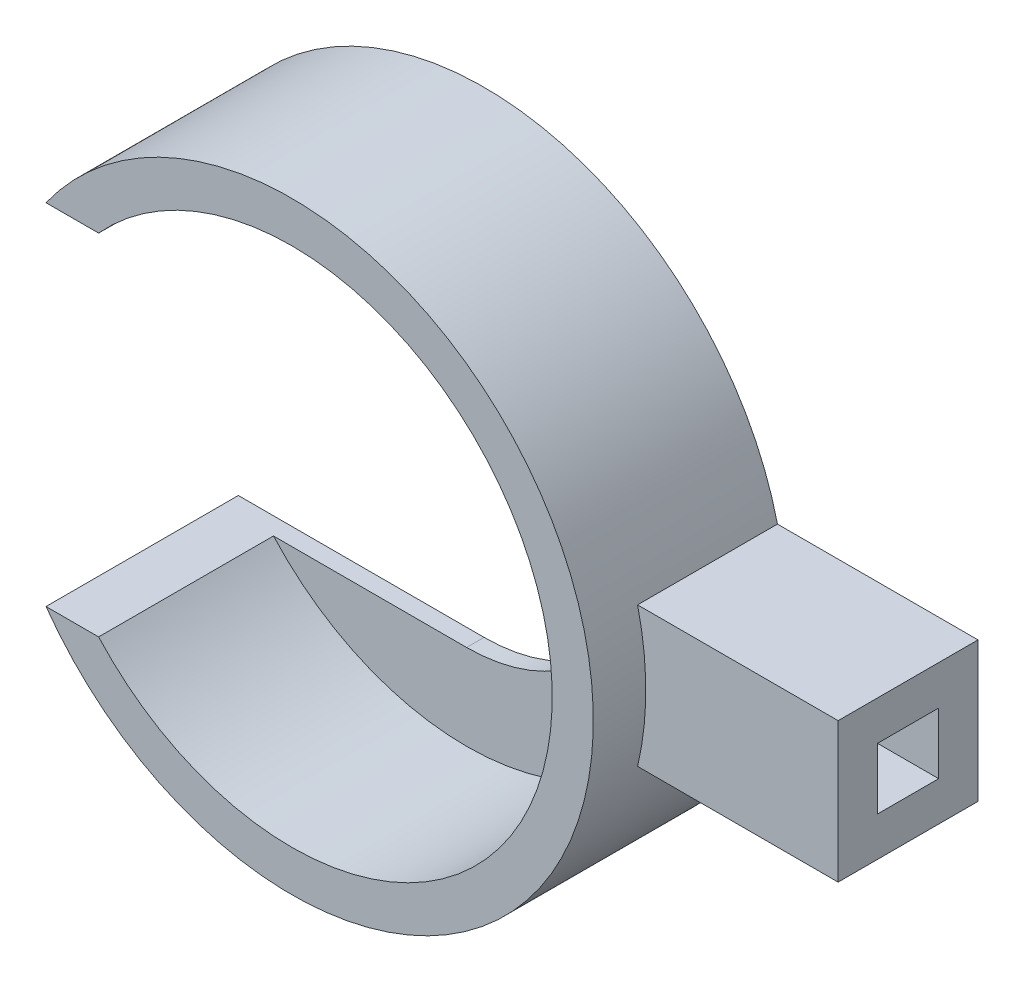
SolidWorks part; units mm, degrees
ref_plane "Front Plane" through (0, 0, 0) normal (0, 0, 1) x (1, 0, 0)
ref_plane "Top Plane" through (0, 0, 0) normal (0, 1, 0) x (1, 0, 0)
ref_plane "Right Plane" through (0, 0, 0) normal (1, 0, 0) x (0, 0, -1)
sketch "Sketch1" plane through (0, 0, 0) normal (0, 0, 1) x (1, 0, 0)
  circle A0 centre (0, 0) radius 14.9
  circle A1 centre (0, 0) radius 17.25
extrude "Boss-Extrude1" add sketch "Sketch1" along normal blind 10
sketch "Sketch2" plane through (0, 0, 0) normal (0, 0, -1) x (-1, 0, 0)
  circle A0 centre (0, 0) radius 17.25
  circle A1 centre (0, 0) radius 10
extrude "Boss-Extrude3" add sketch "Sketch2" along normal blind 1
sketch "Sketch3" plane through (0, 0, -1) normal (0, 0, -1) x (-1, 0, 0)
  line L0 (0, 10) -> (14.0557, 10)
  line L1 (0, -10) -> (14.0557, -10)
  circle A0 centre (0, 0) radius 10
  circle A1 centre (0, 0) radius 17.25 construction
  circle A2 centre (0, 0) radius 17.25
  circle M1 centre (0, 0) radius 17.25
  circle M2 centre (0, 0) radius 10
extrude "Cut-Extrude1" cut sketch "Sketch3" against normal through all contours M2 | L1 L0 M2 M1
sketch3d "3DSketch1"
  line L0 (17.25, 0, -1) -> (17.25, -4, -1)
  line L1 (17.25, 0, -1) -> (17.25, 4, -1)
  line L7 (17.25, 0, -1) -> (17.25, 0, 10) construction
  line L8 (17.25, 4, -1) -> (17.25, 4, 7)
  line L10 (17.25, 4, 7) -> (17.25, -4, 7)
  line L11 (17.25, -4, -1) -> (17.25, -4, 7)
  arc A0 (-14.0557, 10, -1) -> (-14.0557, -10, -1) centre (0, 0, -1) ccw construction
  arc A1 (-14.0557, -10, 10) -> (-14.0557, 10, 10) centre (0, 0, 10) ccw construction
  point P5 (0, 0, -18.25)
  point P9 (0, 0, 27.25)
extrude "Boss-Extrude4" add sketch "3DSketch1" along direction (-1, 0, 0) on the side of the normal blind 11 and the other way blind 1.5 contours L11 L10 L8 L1 L0
sketch "Sketch4" plane through (28.25, 0, 0) normal (1, 0, 0) x (0, 0, -1)
  line L0 (1, 0) -> (-7, 0) construction
  line L1 (1, -4) -> (1, 4) construction
  line L2 (-7, 4) -> (-7, -4) construction
  line L3 (-4.75, -1.75) -> (-4.75, 1.75)
  line L4 (-4.75, -1.75) -> (-1.25, -1.75)
  line L5 (-4.75, 1.75) -> (-1.25, 1.75)
  line L6 (-1.25, -1.75) -> (-1.25, 1.75)
  line L7 (-4.75, -1.75) -> (-1.25, 1.75) construction
  line L8 (-4.75, 1.75) -> (-1.25, -1.75) construction
  point P7 (-3, 0)
extrude "Cut-Extrude2" cut sketch "Sketch4" against normal blind 3.5
